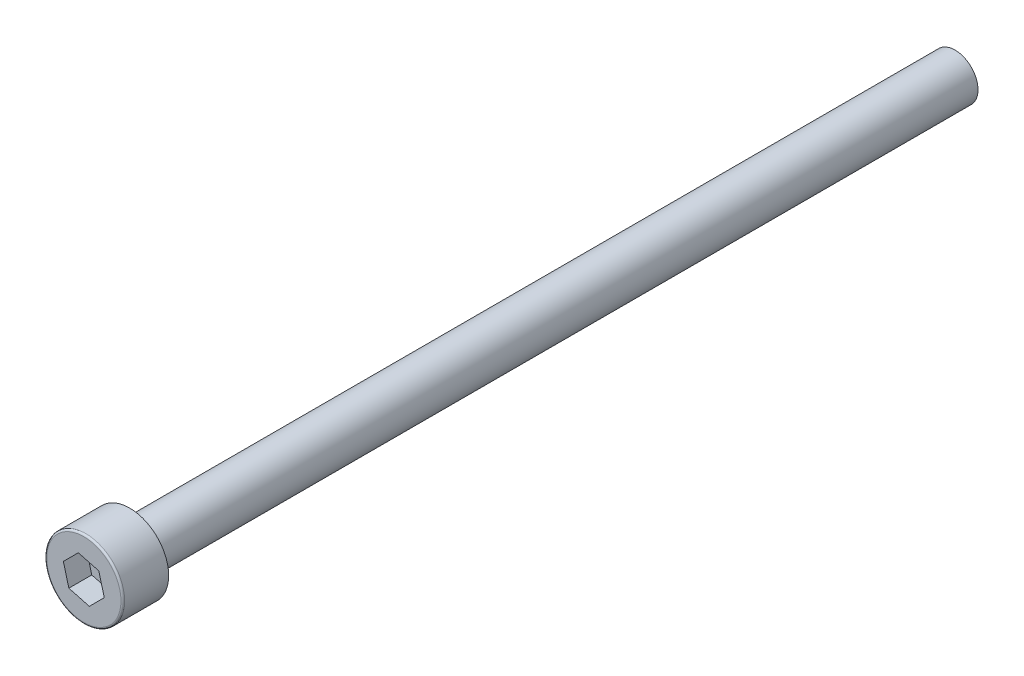
SolidWorks part; units mm, degrees
ref_plane "前视基准面" through (0, 0, 0) normal (0, 0, 1) x (1, 0, 0)
ref_plane "上视基准面" through (0, 0, 0) normal (0, 1, 0) x (1, 0, 0)
ref_plane "右视基准面" through (0, 0, 0) normal (1, 0, 0) x (0, 0, -1)
sketch "草图1" plane through (0, 0, 0) normal (0, 0, 1) x (1, 0, 0)
  circle A0 centre (0, 0) radius 4.25
  dimension "D1" = 8.5
extrude "凸台-拉伸1" add sketch "草图1" along normal blind 5
sketch "草图2" plane through (0, 0, 5) normal (0, 0, 1) x (1, 0, 0)
  line L1 (-1.633, -1.633) -> (0.5977, -2.2307)
  line L2 (0.5977, -2.2307) -> (2.2307, -0.5977)
  line L3 (2.2307, -0.5977) -> (1.633, 1.633)
  line L4 (1.633, 1.633) -> (-0.5977, 2.2307)
  line L5 (-0.5977, 2.2307) -> (-2.2307, 0.5977)
  line L6 (-2.2307, 0.5977) -> (-1.633, -1.633)
  circle A0 centre (0, 0) radius 2 construction
  dimension "D1" = 4
extrude "切除-拉伸1" cut sketch "草图2" against normal blind 2.5
sketch "草图3" plane through (0, 0, 0) normal (0, 0, -1) x (-1, 0, 0)
  circle A0 centre (0, 0) radius 2.5
  dimension "D1" = 5
extrude "凸台-拉伸2" add sketch "草图3" along normal blind 90
fillet "圆角1" radius 0.2 1 edges at (4.25, 0, 5)
